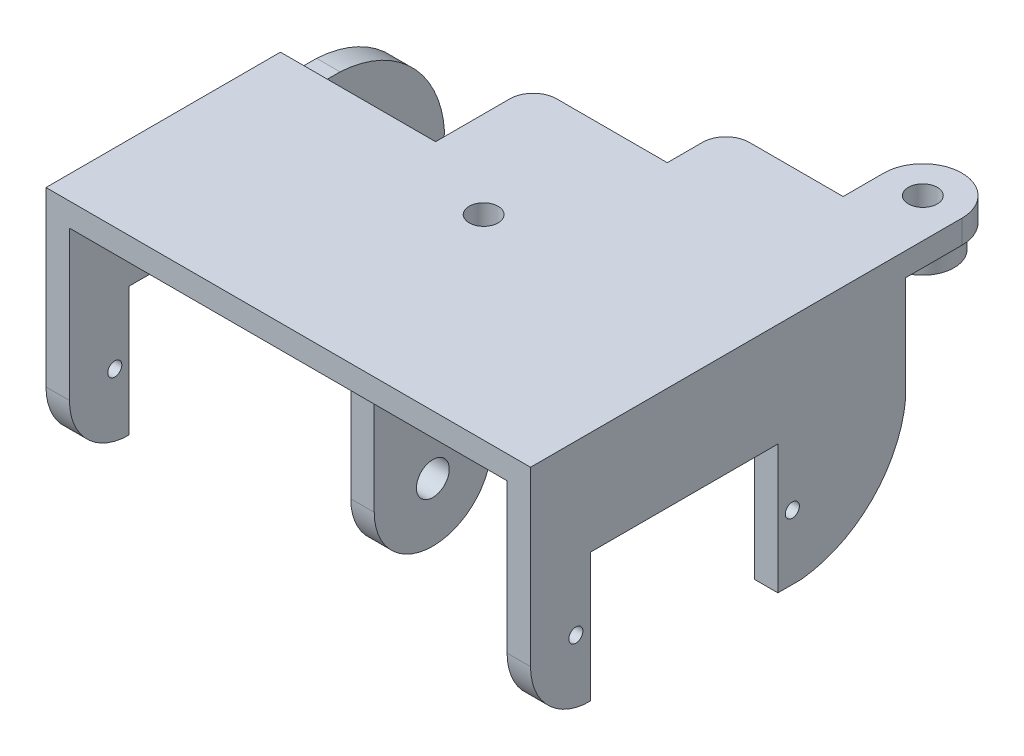
SolidWorks part; units mm, degrees
ref_plane "Front Plane" through (0, 0, 0) normal (0, 0, 1) x (1, 0, 0)
ref_plane "Top Plane" through (0, 0, 0) normal (0, 1, 0) x (1, 0, 0)
ref_plane "Right Plane" through (0, 0, 0) normal (1, 0, 0) x (0, 0, -1)
sketch "Sketch1" plane through (0, 0, 0) normal (0, 1, 0) x (1, 0, 0)
  line L0 (52, 50) -> (52, 55.2)
  line L1 (0, 0) -> (62, 0)
  line L2 (0, 0) -> (0, 50)
  line L4 (62, 0) -> (62, 50)
  line L5 (62, 55.2) -> (62, 50)
  line L6 (52, 50) -> (0, 50)
  line L7 (52, 50) -> (37, 50)
  line L8 (37, 50) -> (37, 42.5)
  line L9 (37, 42.5) -> (19.85, 42.5)
  line L10 (19.85, 42.5) -> (19.85, 30)
  line L11 (19.85, 30) -> (0, 30)
  line L12 (0, 30) -> (0, 0)
  arc A0 (52, 55.2) -> (62, 55.2) centre (57, 55.2) cw
  circle A1 centre (31, 25) radius 1.85
  circle A2 centre (57, 55.2) radius 1.85
  point P5 (52, 50)
  point P10 (31, 25)
  point P21 (31, 0)
  point P23 (0, 25)
  dimension "D10" = 3.7
  dimension "D11" = 3.7
  dimension "D1" = 50
  dimension "D2" = 62
  dimension "D3" = 10
  dimension "D4" = 5.2
  dimension "D5" = 15
  dimension "D6" = 7.5
  dimension "D8" = 12.5
  dimension "D9" = 19.85
extrude "Boss-Extrude1" add sketch "Sketch1" against normal blind 3 contours A0 L0 L6 L8 L9 L10 L11 L2 L1 L4 L5 A1
sketch "Sketch2" plane through (0, -3, 0) normal (0, -1, 0) x (-1, 0, 0)
  line L0 (-62, 0) -> (-62, 55.2) construction
  line L1 (0, 0) -> (-62, 0) construction
  line L2 (-62, 48) -> (-59, 48)
  line L3 (-62, 48) -> (-62, 0)
  line L4 (-62, 0) -> (-59, 0)
  line L5 (-59, 48) -> (-59, 0)
  line L6 (-31, 0) -> (-31, 82.5445) construction
  line L7 (0, 0) -> (-3, 0)
  line L8 (-3, 48) -> (-3, 0)
  line L9 (0, 48) -> (0, 0)
  line L10 (0, 48) -> (-3, 48)
  point P0 (-62, 48)
  dimension "D1" = 48
  dimension "D2" = 3
extrude "Boss-Extrude2" add sketch "Sketch2" along normal blind 26.75
sketch "Sketch4" plane through (62, 0, 0) normal (-1, 0, 0) x (0, 0, 1)
  line L0 (-30, -3) -> (-48, -3) construction
  line L1 (0, 0) -> (-30, 0) construction
  line L2 (0, -29.75) -> (0, 0) construction
  line L3 (-31.65, -13.25) -> (-7.65, -13.25)
  line L4 (-7.65, -13.25) -> (-7.65, -29.75)
  line L5 (0, -29.75) -> (-48, -29.75) construction
  line L6 (-31.65, -13.25) -> (-31.65, -29.75)
  line L7 (-31.65, -29.75) -> (-7.65, -29.75)
  line L8 (-30, -3) -> (-33.65, -3)
  line L9 (-48, -29.75) -> (-48, -3) construction
  line L10 (-19.65, -13.25) -> (-19.65, 0) construction
  line L11 (0, 0) -> (-55.2, 0) construction
  arc A1 (-7.65, -29.75) -> (0, -22.1) centre (-7.65, -22.1) ccw
  circle A2 centre (-33.5, -21.5) radius 0.9
  arc A3 (-48, -16.375) -> (-31.65, -29.75) centre (-33.1375, -14.8875) ccw
  circle A4 centre (-5.8, -21.5) radius 0.9
  point P0 (-33.65, -3)
  point P1 (-31.65, -13.25)
  point P7 (-7.65, -13.25)
  point P20 (-33.5, -21.5)
  point P24 (-48, -16.375)
  point P38 (-31.65, -21.5)
  line M23 (0, 0) -> (0, -29.75)
  line M24 (0, -29.75) -> (-48, -29.75)
  line M25 (-48, -29.75) -> (-48, -3)
  dimension "D6" = 1.8
  dimension "D1" = 3.65
  dimension "D2" = 13.25
  dimension "D3" = 7.65
  dimension "D4" = 24
  dimension "D5" = 1.85
ref_plane "Plane2" through (31, 0, 0) normal (1, 0, 0) x (0, 0, -1)
extrude "Cut-Extrude3" cut sketch "Sketch4" along normal blind 3 contours A3 M25 M24 | L6 L3 L4 M24 | A1 M24 M23 | A2 | A4
mirror "Mirror2" about plane through (31, 0, 0) normal (1, 0, 0) of "Cut-Extrude3"
sketch "Sketch5" plane through (0, 0, 0) normal (-1, 0, 0) x (0, 0, 1)
  line L0 (-30, -3) -> (-48, -3) construction
  arc A0 (-48, -16.375) -> (-33, -3) centre (-33.8125, -17.1875) cw
  point P0 (-33, -3)
  point P1 (-48, -16.375)
  dimension "D1" = 3
extrude "Cut-Extrude4" cut sketch "Sketch5" against normal blind 3 and the other way through all
sketch "Sketch6" plane through (0, -3, 0) normal (0, -1, 0) x (-1, 0, 0)
  line L1 (-35.5, 26.3997) -> (-32.5, 26.3997)
  line L2 (-35.5, 26.3997) -> (-35.5, 41.3997)
  line L3 (-3, 0) -> (-59, 0) construction
  line L4 (-32.5, 21.5) -> (-35.5, 21.5)
  line L5 (-32.5, 21.5) -> (-32.5, 6.5)
  line L6 (-32.5, 6.5) -> (-35.5, 6.5)
  line L7 (-35.5, 21.5) -> (-35.5, 6.5)
  line L8 (-32.5, 21.5) -> (-35.5, 6.5) construction
  line L9 (-32.5, 6.5) -> (-35.5, 21.5) construction
  line L10 (-35.5, 41.3997) -> (-32.5, 41.3997)
  line L11 (-32.5, 26.3997) -> (-32.5, 41.3997)
  line L12 (-35.5, 26.3997) -> (-32.5, 41.3997) construction
  line L13 (-35.5, 41.3997) -> (-32.5, 26.3997) construction
  line L14 (-62, 31.65) -> (-62, 7.65) construction
  point P0 (-34, 33.8997)
  point P6 (-34, 14)
  dimension "D1" = 15
  dimension "D2" = 3
  dimension "D3" = 14
  dimension "D4" = 3
  dimension "D5" = 15
  dimension "D7" = 28
extrude "Boss-Extrude3" add sketch "Sketch6" along normal blind 26.75
sketch "Sketch7" plane through (32.5, 0, 0) normal (-1, 0, 0) x (0, 0, 1)
  line L0 (0, 0) -> (-30, 0) construction
  line L1 (-6.5, -21.5) -> (-21.5, -21.5) construction
  line L2 (-6.5, -29.75) -> (-6.5, -3) construction
  line L3 (-21.5, -29.75) -> (-21.5, -3) construction
  line L4 (-6.5, -29.75) -> (-21.5, -29.75) construction
  circle A0 centre (-14, -21.5) radius 2.1
  arc A1 (-21.5, -21.5) -> (-6.5, -21.5) centre (-14, -21.5) ccw
  point P12 (-14, -29.75)
  line M3 (-21.5, -3) -> (-21.5, -29.75)
  line M4 (-21.5, -29.75) -> (-6.5, -29.75)
  line M5 (-6.5, -29.75) -> (-6.5, -3)
  dimension "D2" = 4.2
  dimension "D1" = 21.5
extrude "Cut-Extrude5" cut sketch "Sketch7" against normal blind 6 contours A1 M3 M4 M5 | A0 L1 | L1 A0
sketch "Sketch8" plane through (32.5, 0, 0) normal (-1, 0, 0) x (0, 0, 1)
  line L1 (0, 0) -> (-30, 0) construction
  line L2 (-26.3997, -29.75) -> (-41.3997, -29.75) construction
  line L3 (-26.3997, -29.75) -> (-26.3997, -3) construction
  line L4 (-41.3997, -29.75) -> (-41.3997, -3) construction
  circle A0 centre (-33.8997, -21.5) radius 2.1
  arc A1 (-41.3997, -21.5) -> (-26.3997, -21.5) centre (-33.8997, -21.5) ccw
  point P6 (-33.8997, -29.75)
  point P9 (-41.3997, -21.5)
  point P10 (-26.3997, -21.5)
  point P11 (-41.3997, -21.5)
  line M3 (-41.3997, -3) -> (-41.3997, -29.75)
  line M4 (-41.3997, -29.75) -> (-26.3997, -29.75)
  line M5 (-26.3997, -29.75) -> (-26.3997, -3)
  dimension "D2" = 4.2
  dimension "D1" = 21.5
extrude "Cut-Extrude6" cut sketch "Sketch8" against normal blind 6 contours A0 | A1 M3 M4 M5
fillet "Fillet2" radius 3 2 edges at (37, -1.5, -50) (19.85, -1.5, -42.5)
sketch "Sketch10" plane through (0, -3, 0) normal (0, -1, 0) x (1, 0, 0)
  circle A0 centre (57, -55.2) radius 1.85
  circle A1 centre (57, -55.2) radius 4
  dimension "D1" = 3.7
  dimension "D2" = 8
extrude "Boss-Extrude4" add sketch "Sketch10" along normal blind 3
